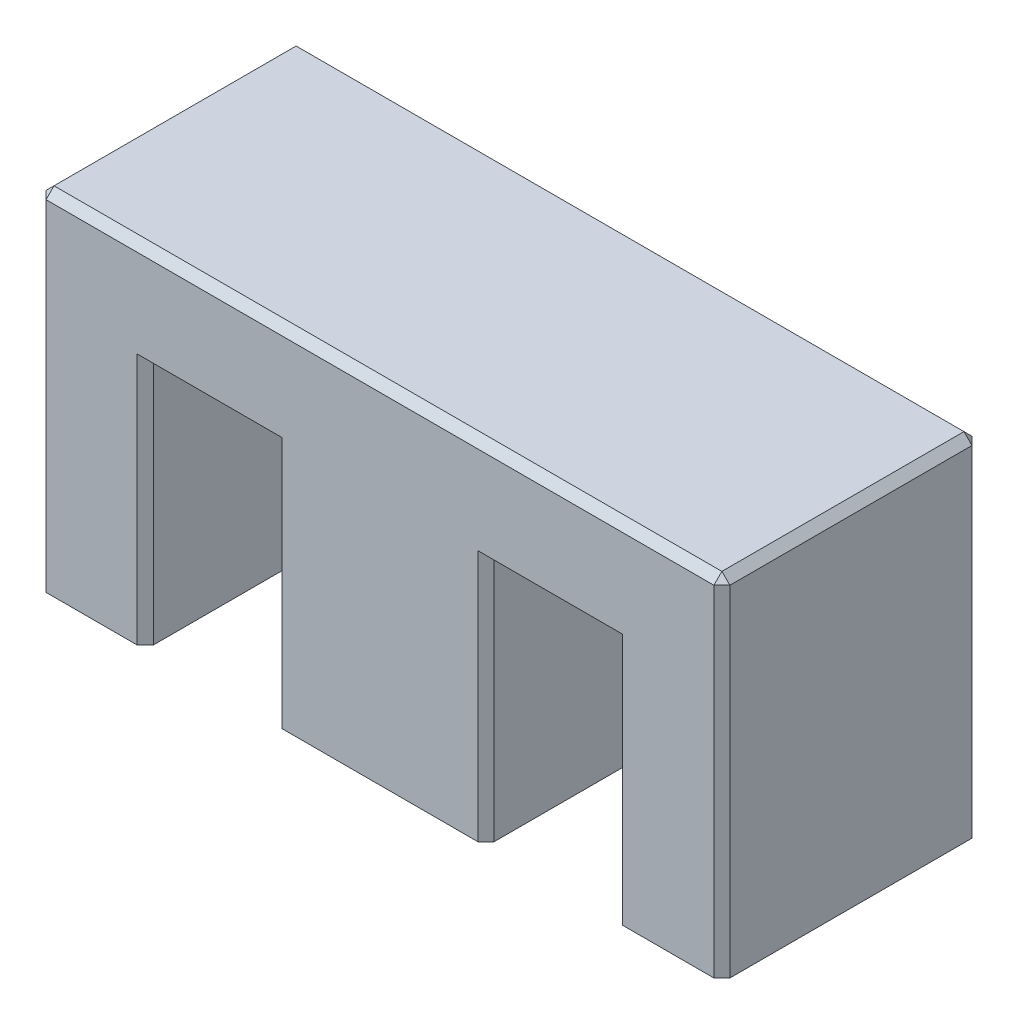
SolidWorks part; units mm, degrees
ref_plane "Front Plane" through (0, 0, 0) normal (0, 0, 1) x (1, 0, 0)
ref_plane "Top Plane" through (0, 0, 0) normal (0, 1, 0) x (1, 0, 0)
ref_plane "Right Plane" through (0, 0, 0) normal (1, 0, 0) x (0, 0, -1)
sketch "Sketch1" plane through (0, 0, 0) normal (0, 0, 1) x (1, 0, 0)
  line L0 (0, 41.0398) -> (0, -33.7699) construction
  line L1 (13.25, -21.75) -> (-13.25, -21.75)
  line L2 (-13.25, -21.75) -> (-13.25, 8.75)
  line L3 (-13.25, 8.75) -> (-29.325, 8.75)
  line L4 (-29.325, 8.75) -> (-29.325, -21.75)
  line L5 (-29.325, -21.75) -> (-42.725, -21.75)
  line L6 (-42.725, -21.75) -> (-42.725, 21.75)
  line L7 (-42.725, 21.75) -> (42.725, 21.75)
  line L8 (13.25, -21.75) -> (13.25, 8.75)
  line L9 (13.25, 8.75) -> (29.325, 8.75)
  line L10 (29.325, 8.75) -> (29.325, -21.75)
  line L11 (29.325, -21.75) -> (42.725, -21.75)
  line L12 (42.725, -21.75) -> (42.725, 21.75)
  point P11 (-42.725, 0)
  point P12 (0, -21.75)
  point P17 (0, 21.75)
  dimension "D1" = 26.5
  dimension "D2" = 58.65
  dimension "D3" = 85.45
  dimension "D4" = 43.5
  dimension "D5" = 13
extrude "Boss-Extrude1" add sketch "Sketch1" along normal mid plane 32.25
chamfer "Chamfer1" distance 1 angle 45 20 edges at (42.725, 21.75, 0) (0, 21.75, 16.125) (-42.725, 21.75, 0) (0, 21.75, -16.125) (-29.325, -6.5, -16.125) (-21.2875, 8.75, -16.125) (-13.25, -6.5, -16.125) (13.25, -6.5, -16.125) (21.2875, 8.75, -16.125) (29.325, -6.5, -16.125) (42.725, 0, -16.125) (-42.725, 0, -16.125) (-42.725, 0, 16.125) (42.725, 0, 16.125) (29.325, -6.5, 16.125) (21.2875, 8.75, 16.125) (13.25, -6.5, 16.125) (-13.25, -6.5, 16.125) (-21.2875, 8.75, 16.125) (-29.325, -6.5, 16.125)
